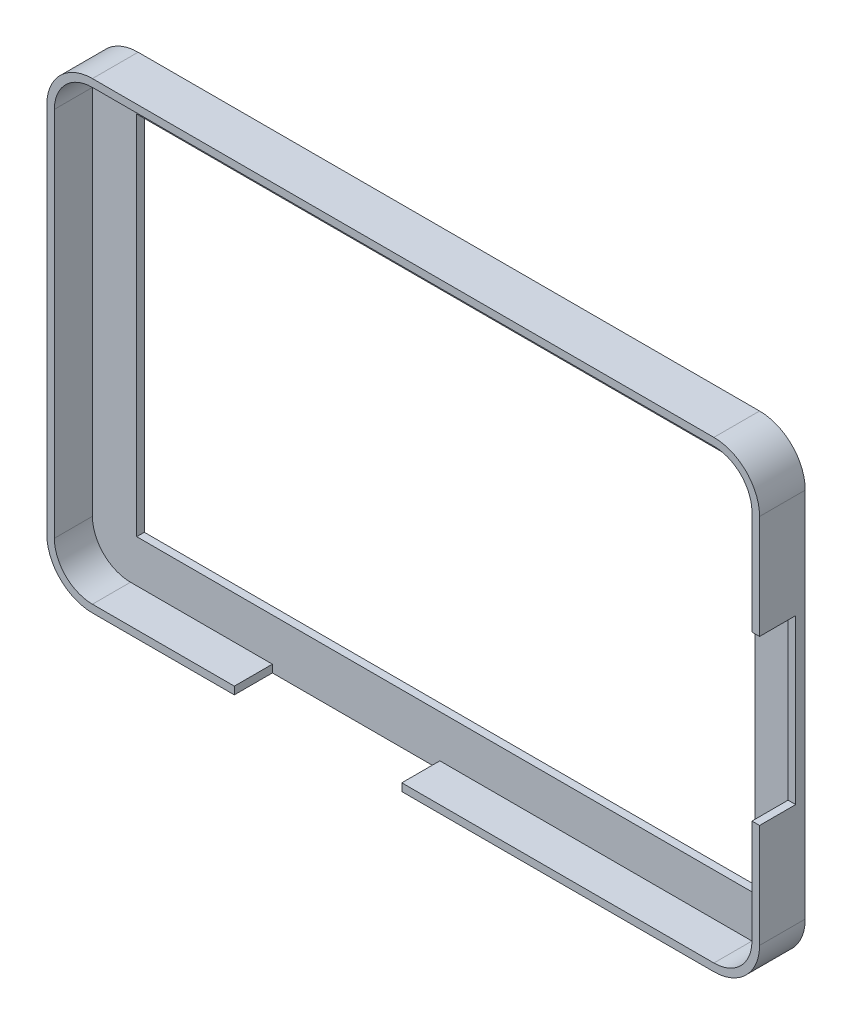
SolidWorks part; units mm, degrees
ref_plane "Ebene vorne" through (0, 0, 0) normal (1, 0, 0) x (0, 1, 0)
ref_plane "Ebene oben" through (0, 0, 0) normal (0, 0, 1) x (0, 1, 0)
ref_plane "Ebene rechts" through (0, 0, 0) normal (0, 1, 0) x (-1, 0, 0)
sketch "Skizze1" plane through (0, 0, 0) normal (0, 0, 1) x (0, 1, 0)
  line L0 (-30.4, -46.82) -> (30.4, -46.82)
  line L1 (-30.4, -46.82) -> (-30.4, 46.82)
  line L2 (-30.4, 46.82) -> (30.4, 46.82)
  line L3 (30.4, -46.82) -> (30.4, 46.82)
  line L4 (-30.4, -46.82) -> (30.4, 46.82) construction
  line L5 (-30.4, 46.82) -> (30.4, -46.82) construction
  point P0 (0, 0)
  point P5 (0, 0)
  dimension "D1" = 60.8
  dimension "D2" = 93.64
extrude "Aufsatz-Linear austragen1" add sketch "Skizze1" along normal blind 6
fillet "Verrundung1" radius 6 4 edges at (46.82, -30.4, 3) (-46.82, -30.4, 3) (-46.82, 30.4, 3) (46.82, 30.4, 3)
shell "Wandung1" thickness 1
sketch "Skizze2" plane through (46.82, 0, 0) normal (1, 0, 0) x (0, 1, 0)
  line L0 (-24.4, 6) -> (24.4, 6) construction
  line L1 (-10.75, 10.75) -> (10.75, 10.75)
  line L2 (-10.75, 10.75) -> (-10.75, 1.25)
  line L3 (-10.75, 1.25) -> (10.75, 1.25)
  line L4 (10.75, 10.75) -> (10.75, 1.25)
  line L5 (-10.75, 10.75) -> (10.75, 1.25) construction
  line L6 (-10.75, 1.25) -> (10.75, 10.75) construction
  point P0 (0, 6)
  dimension "D1" = 21.5
  dimension "D2" = 9.5
extrude "Schnitt-Linear austragen1" cut sketch "Skizze2" against normal blind 6
sketch "Skizze3" plane through (0, -30.4, 0) normal (0, -1, 0) x (1, 0, 0)
  line L0 (-40.82, 6) -> (40.82, 6) construction
  line L1 (-0.18, 6) -> (-22.18, 6)
  line L2 (-0.18, 6) -> (-0.18, 1)
  line L3 (-0.18, 1) -> (-22.18, 1)
  line L4 (-22.18, 6) -> (-22.18, 1)
  dimension "D1" = 22
  dimension "D2" = 5
  dimension "D3" = 41
extrude "Schnitt-Linear austragen2" cut sketch "Skizze3" against normal blind 6
sketch "Skizze4" plane through (0, 0, 0) normal (0, 0, -1) x (1, 0, 0)
  line L1 (-40.0035, 23.808) -> (41.2523, 23.808)
  line L2 (-40.0035, 23.808) -> (-40.0035, -24.277)
  line L3 (-40.0035, -24.277) -> (41.2523, -24.277)
  line L4 (41.2523, 23.808) -> (41.2523, -24.277)
extrude "Schnitt-Linear austragen3" cut sketch "Skizze4" against normal blind 6
